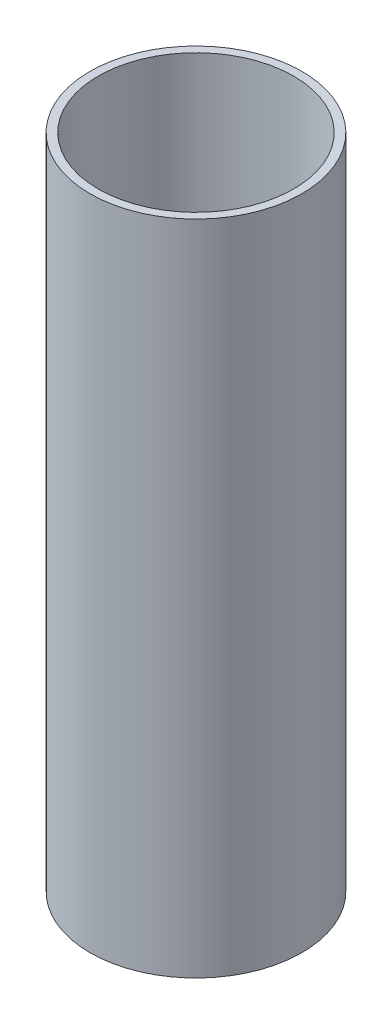
SolidWorks part; units mm, degrees
material "ABS PC"
ref_plane "Front Plane" through (0, 0, 0) normal (0, 0, 1) x (1, 0, 0)
ref_plane "Top Plane" through (0, 0, 0) normal (0, 1, 0) x (1, 0, 0)
ref_plane "Right Plane" through (0, 0, 0) normal (1, 0, 0) x (0, 0, -1)
sketch "Sketch1" plane through (0, 0, 0) normal (0, 1, 0) x (1, 0, 0)
  circle A0 centre (0, 0) radius 17.85
  circle A1 centre (0, 0) radius 19.35
  dimension "D1" = 38.7
  dimension "D2" = 35.7
extrude "Boss-Extrude1" add sketch "Sketch1" along normal mid plane 120
